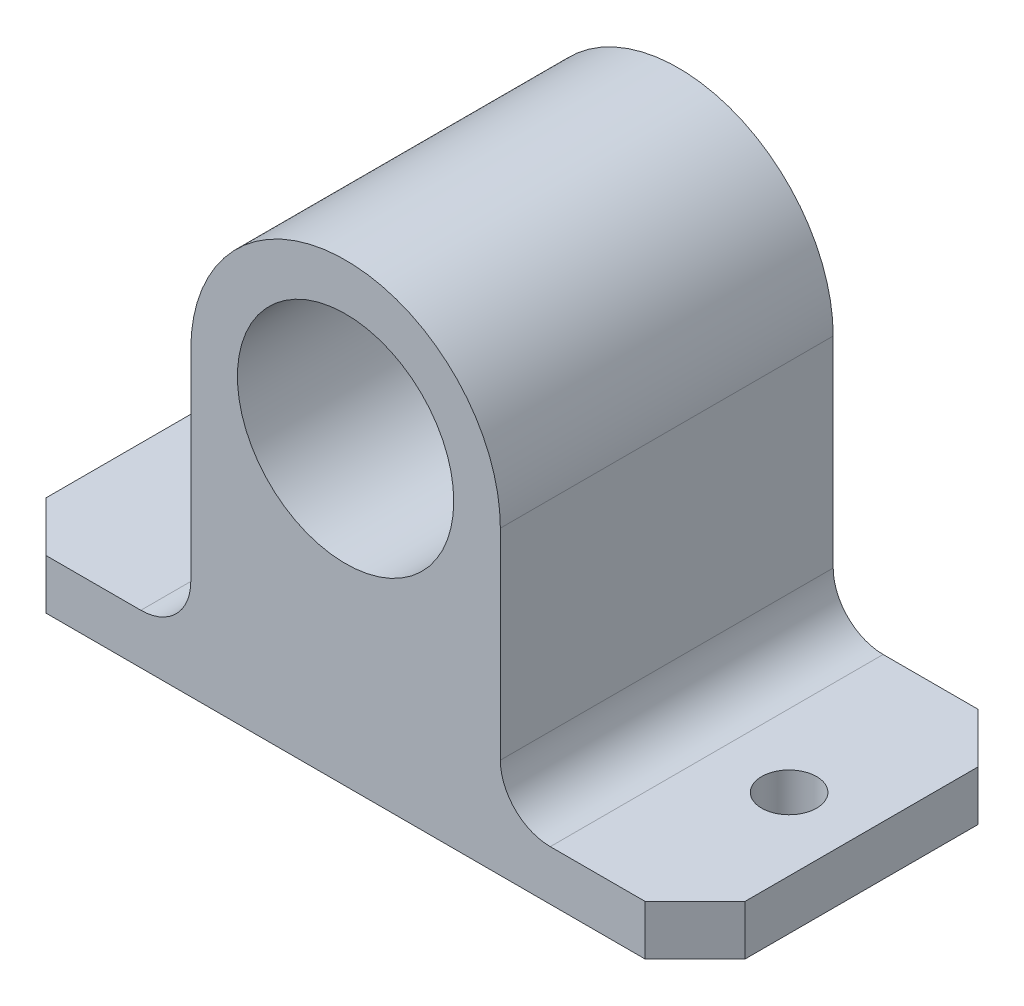
SolidWorks part; units mm, degrees
ref_plane "Front Plane" through (0, 0, 0) normal (0, 0, 1) x (1, 0, 0)
ref_plane "Top Plane" through (0, 0, 0) normal (0, 1, 0) x (1, 0, 0)
ref_plane "Right Plane" through (0, 0, 0) normal (1, 0, 0) x (0, 0, -1)
sketch "Sketch1" plane through (0, 0, 0) normal (0, 0, 1) x (1, 0, 0)
  line L0 (0, 0) -> (0, -18.0724) construction
  line L1 (-21, -18.0724) -> (21, -18.0724)
  line L2 (-21, -18.0724) -> (-21, -15.0724)
  line L3 (-21, -15.0724) -> (-12.3, -15.0724)
  line L4 (21, -18.0724) -> (21, -15.0724)
  line L6 (-9.3, 0) -> (-9.3, -12.0724)
  line L8 (9.3, 0) -> (9.3, -12.0724)
  line L9 (12.3, -15.0724) -> (21, -15.0724)
  circle A0 centre (0, 0) radius 6.5
  arc A1 (9.3, 0) -> (-9.3, 0) centre (0, 0) ccw
  arc A2 (12.3, -15.0724) -> (9.3, -12.0724) centre (12.3, -12.0724) cw
  arc A3 (-9.3, -12.0724) -> (-12.3, -15.0724) centre (-12.3, -12.0724) cw
  point P3 (9.3, 0)
  point P15 (9.3, -15.0724)
  dimension "D1" = 13
  dimension "D2" = 2.8
  dimension "D5" = 3
  dimension "D3" = 3
  dimension "D4" = 42
extrude "Boss-Extrude1" add sketch "Sketch1" along normal blind 20
chamfer "Chamfer1" distance 3 angle 45 4 edges at (-21, -16.5724, 20) (-21, -16.5724, 0) (21, -16.5724, 0) (21, -16.5724, 20)
sketch "Sketch2" plane through (0, -15.0724, 0) normal (0, 1, 0) x (1, 0, 0)
  line L0 (21, -10) -> (12.3, -10) construction
  line L1 (21, -17) -> (21, -3) construction
  line L2 (12.3, -20) -> (12.3, 0) construction
  line L3 (-12.3, -10) -> (-21, -10) construction
  line L4 (-12.3, -20) -> (-12.3, 0) construction
  line L5 (-21, -17) -> (-21, -3) construction
  circle A0 centre (16.65, -10) radius 1.65
  circle A1 centre (-16.65, -10) radius 1.65
  dimension "D1" = 3.3
  dimension "D2" = 3.3
extrude "Cut-Extrude1" cut sketch "Sketch2" against normal blind 20
